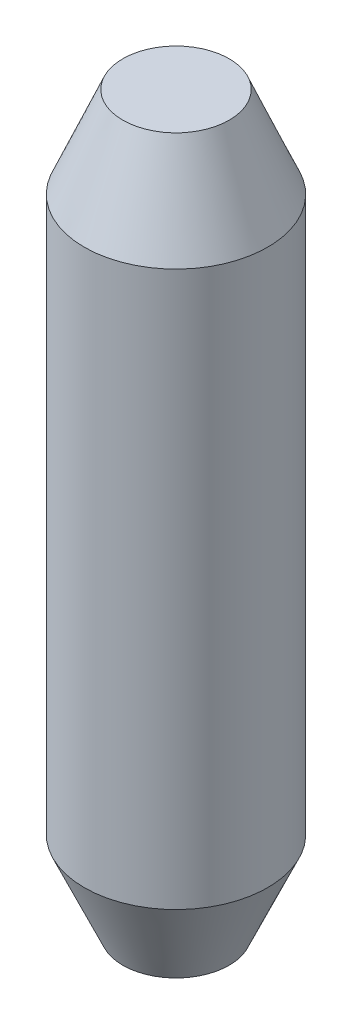
SolidWorks part; units mm, degrees
ref_plane "Front Plane" through (0, 0, 0) normal (0, 0, 1) x (1, 0, 0)
ref_plane "Top Plane" through (0, 0, 0) normal (0, 1, 0) x (1, 0, 0)
ref_plane "Right Plane" through (0, 0, 0) normal (1, 0, 0) x (0, 0, -1)
sketch "Sketch1" plane through (0, 0, 0) normal (0, 1, 0) x (1, 0, 0)
  circle A0 centre (0, 0) radius 2.3813
  dimension "D1" = 4.7625
extrude "Boss-Extrude1" add sketch "Sketch1" along normal blind 19
chamfer "Chamfer1" distance 1 angle 66 1 edges at (0, 0, 2.3813)
chamfer "Chamfer2" distance 1 angle 67 1 edges at (0, 19, 2.3813)
